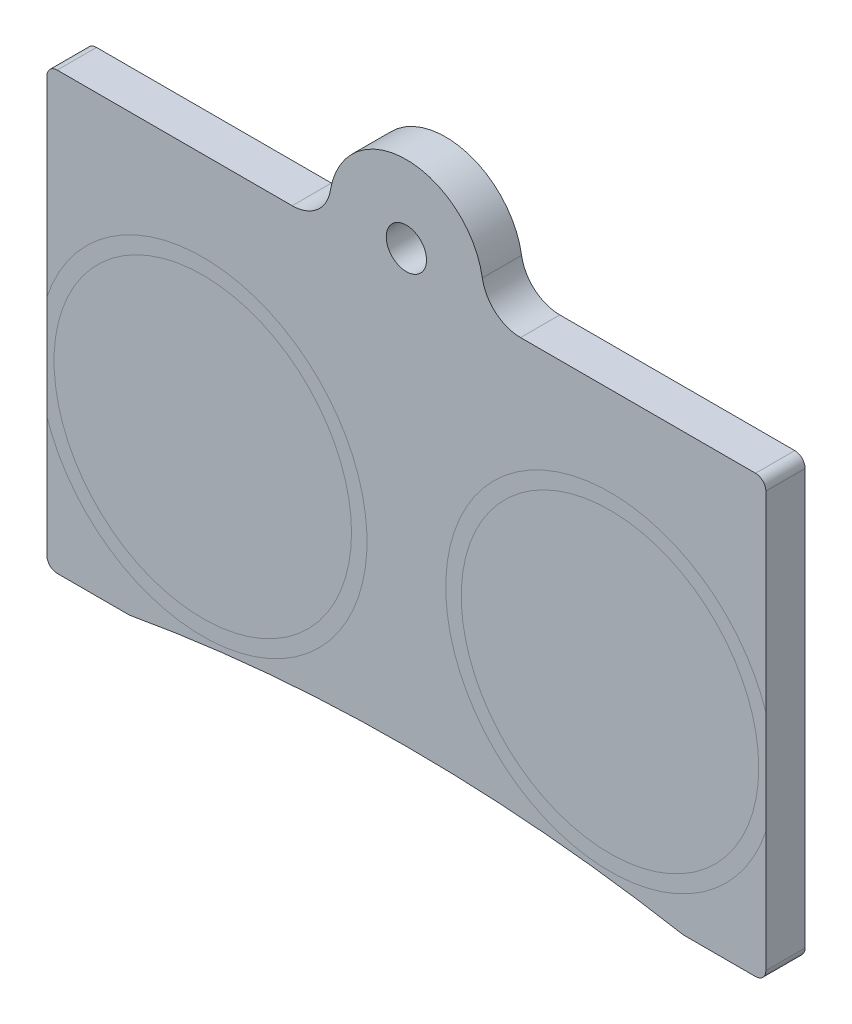
SolidWorks part; units mm, degrees
ref_plane "Front Plane" through (0, 0, 0) normal (0, 0, 1) x (1, 0, 0)
ref_plane "Top Plane" through (0, 0, 0) normal (0, 1, 0) x (1, 0, 0)
ref_plane "Right Plane" through (0, 0, 0) normal (1, 0, 0) x (0, 0, -1)
sketch "Sketch1" plane through (0, 0, 0) normal (0, 0, 1) x (1, 0, 0)
  line L0 (26.8, -44.15) -> (33.8, -44.15)
  line L1 (-33.8, -1.95) -> (-11.0544, -1.95)
  line L2 (-34.8, -2.95) -> (-34.8, -43.15)
  line L3 (-33.8, -44.15) -> (-26.8, -44.15)
  line L4 (34.8, -2.95) -> (34.8, -43.15)
  line L5 (0, -41.75) -> (34.8, -41.75) construction
  line L6 (11.0544, -1.95) -> (33.8, -1.95)
  circle A0 centre (0, 0) radius 1.95
  arc A1 (7.3532, 1.1973) -> (-7.3532, 1.1973) centre (0, 0) ccw
  arc A2 (-26.8, -44.15) -> (26.8, -44.15) centre (0, -192.5833) cw
  arc A3 (-34.8, -43.15) -> (-33.8, -44.15) centre (-33.8, -43.15) ccw
  arc A4 (-33.8, -1.95) -> (-34.8, -2.95) centre (-33.8, -2.95) ccw
  arc A5 (33.8, -1.95) -> (34.8, -2.95) centre (33.8, -2.95) cw
  arc A6 (33.8, -44.15) -> (34.8, -43.15) centre (33.8, -43.15) ccw
  arc A7 (-7.3532, 1.1973) -> (-11.0544, -1.95) centre (-11.0544, 1.8) cw
  arc A8 (7.3532, 1.1973) -> (11.0544, -1.95) centre (11.0544, 1.8) ccw
  point P12 (-34.8, -44.15)
  point P23 (34.8, -44.15)
  point P28 (7.1903, -1.95)
  dimension "D3" = 3.9
  dimension "D6" = 34.8
  dimension "D8" = 1
  dimension "D9" = 3.75
  dimension "D10" = 5.5
  dimension "D1" = 69.6
  dimension "D2" = 42.2
  dimension "D4" = 8
  dimension "D5" = 8
  dimension "D7" = 2.4
extrude "Extrude1" add sketch "Sketch1" along normal blind 3.8
sketch "Sketch3" plane through (0, 0, 3.8) normal (0, 0, 1) x (1, 0, 0)
  line L30 (-34.8, -21.4757) -> (-34.8, -31.496)
  line L31 (-34.8, -2.95) -> (-34.8, -43.15) construction
  line L32 (34.8, -21.4757) -> (34.8, -31.496)
  line L33 (34.8, -43.15) -> (34.8, -2.95) construction
  arc A1 (-34.8, -31.496) -> (-34.8, -21.4757) centre (-19.71, -26.4858) ccw construction
  arc A8 (34.8, -31.496) -> (34.8, -21.4757) centre (19.71, -26.4858) cw construction
  arc A37 (-34.8, -31.496) -> (-34.8, -21.4757) centre (-19.71, -26.4858) ccw
  arc A38 (34.8, -21.4757) -> (34.8, -31.496) centre (19.71, -26.4858) ccw
  circle A39 centre (-19.71, -26.4858) radius 14.4
  circle A40 centre (19.71, -26.4858) radius 14.4
split line "Split Line1"
sketch "Sketch4" plane through (0, 0, 0) normal (0, 0, -1) x (-1, 0, 0)
  line L0 (0, -5.1) -> (33.9, -5.1) construction
  line L2 (-33.9, -11.7179) -> (-33.9, -38.4)
  line L3 (-31.9, -40.4) -> (31.9, -40.4)
  line L4 (33.9, -11.7179) -> (33.9, -38.4)
  line L8 (0, -5.1) -> (0, -40.4) construction
  line L9 (-34.8, -43.15) -> (-34.8, -2.95) construction
  line L10 (34.8, -2.95) -> (34.8, -43.15) construction
  line L11 (11.0544, -1.95) -> (33.8, -1.95) construction
  arc A0 (-32.4672, -9.8) -> (32.4672, -9.8) centre (0, -119.5901) cw
  arc A2 (-33.9, -38.4) -> (-31.9, -40.4) centre (-31.9, -38.4) ccw
  arc A3 (31.9, -40.4) -> (33.9, -38.4) centre (31.9, -38.4) ccw
  arc A4 (32.4672, -9.8) -> (33.9, -11.7179) centre (31.9, -11.7179) cw
  arc A5 (-32.4672, -9.8) -> (-33.9, -11.7179) centre (-31.9, -11.7179) ccw
  dimension "D3" = 2
  dimension "D6" = 114.4901
  dimension "D1" = 7.85
  dimension "D2" = 67.8
  dimension "D4" = 35.3
  dimension "D5" = 30.6
